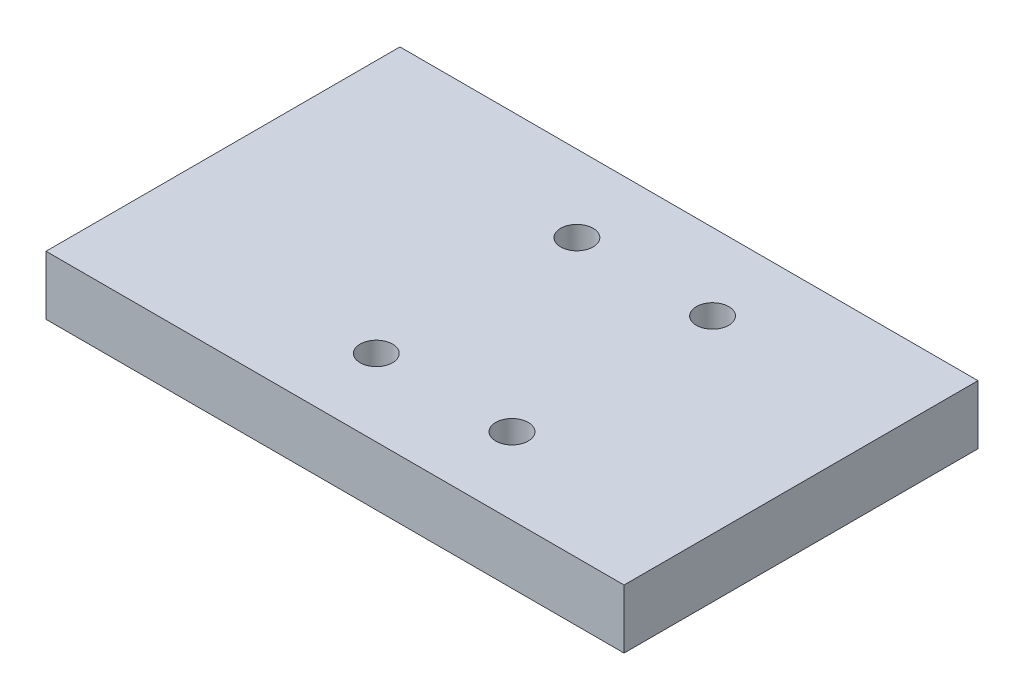
SolidWorks part; units mm, degrees
material "AISI 1020"
ref_plane "Front Plane" through (0, 0, 0) normal (0, 0, 1) x (1, 0, 0)
ref_plane "Top Plane" through (0, 0, 0) normal (0, 1, 0) x (1, 0, 0)
ref_plane "Right Plane" through (0, 0, 0) normal (1, 0, 0) x (0, 0, -1)
sketch "Sketch1" plane through (0, 0, 0) normal (0, 1, 0) x (1, 0, 0)
  line L1 (49, -30) -> (-49, -30)
  line L2 (49, -30) -> (49, 30)
  line L3 (49, 30) -> (-49, 30)
  line L4 (-49, -30) -> (-49, 30)
  line L5 (49, -30) -> (-49, 30) construction
  line L6 (49, 30) -> (-49, -30) construction
  point P0 (0, 0)
  dimension "D1" = 98
  dimension "D2" = 60
extrude "Boss-Extrude1" add sketch "Sketch1" along normal blind 10
hole_wizard "CBORE for M5 Hex Socket Head Cap Screw1" positions "Sketch2" profile "Sketch3" counterbore size "M5" standard "ISO" end condition through all
sketch "Sketch2" plane through (0, 0, 0) normal (0, -1, 0) x (-1, 0, 0)
  line L0 (0, 0) -> (29.3091, 0) construction
  line L2 (49, 30) -> (49, -30) construction
  point P0 (6, 17)
  point P2 (-17, 17)
  point P4 (-17, -17)
  point P6 (6, -17)
  dimension "D1" = 34
  dimension "D2" = 43
  dimension "D3" = 23
sketch "Sketch3" plane through (-6, 0, -17) normal (1, 0, 0) x (0, 0, -1)
  line L0 (0, 0) -> (0, 10)
  line L1 (0, 10) -> (2.75, 10)
  line L3 (2.75, 10) -> (2.75, 5.4)
  line L4 (2.75, 5.4) -> (5, 5.4)
  line L5 (5, 5.4) -> (5, 0)
  line L7 (5, 0) -> (0, 0)
  line L11 (0, -6.35) -> (0, 107.95) construction
  dimension "Thru Hole Dia." = 5.5
  dimension "Thru Hole Depth" = 10
  dimension "C'Bore Dia." = 10
  dimension "C'Bore Depth" = 5.4
